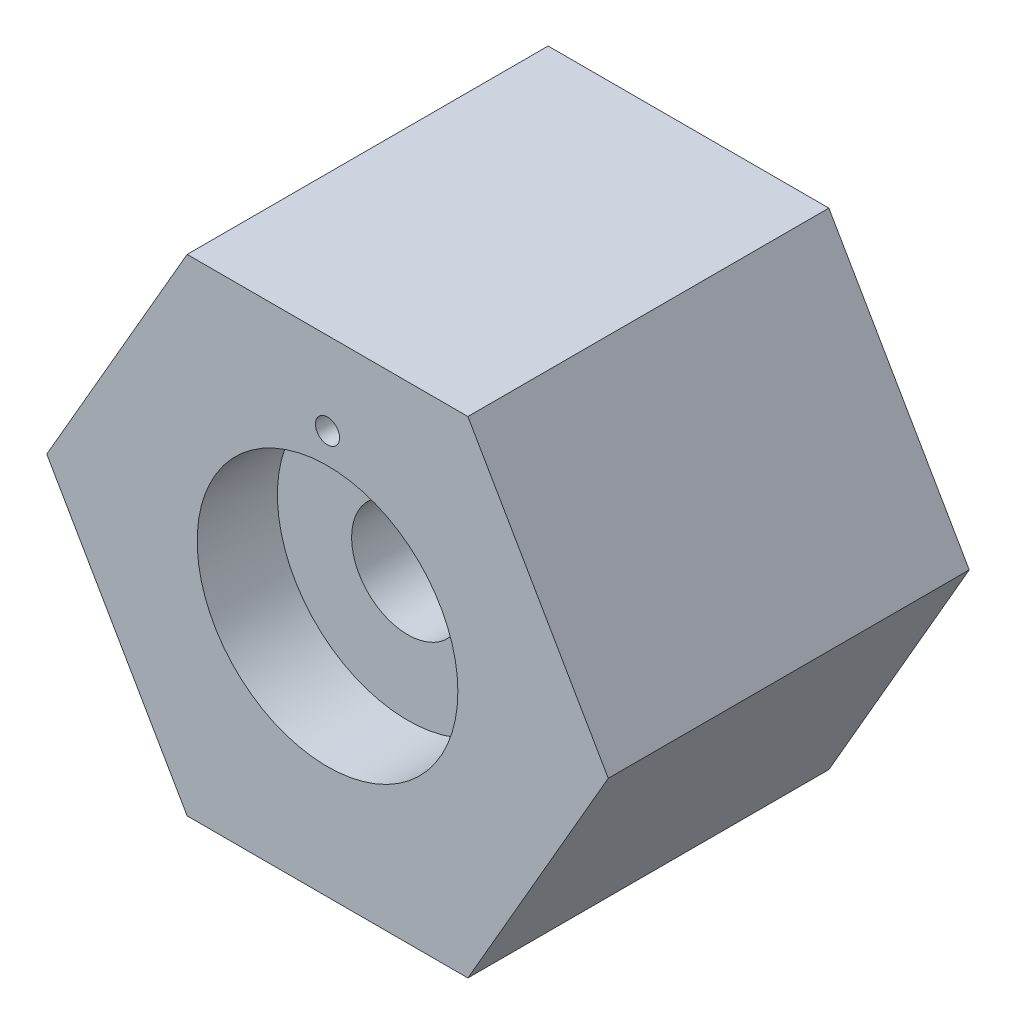
SolidWorks part; units mm, degrees
material "Plain Carbon Steel"
ref_plane "Front Plane" through (0, 0, 0) normal (0, 0, 1) x (1, 0, 0)
ref_plane "Top Plane" through (0, 0, 0) normal (0, 1, 0) x (1, 0, 0)
ref_plane "Right Plane" through (0, 0, 0) normal (1, 0, 0) x (0, 0, -1)
sketch "Sketch1" plane through (0, 0, 0) normal (0, 0, 1) x (1, 0, 0)
  line L8 (-17.5, 30.3109) -> (17.5, 30.3109)
  line L9 (17.5, 30.3109) -> (35, 0)
  line L10 (35, 0) -> (17.5, -30.3109)
  line L11 (17.5, -30.3109) -> (-17.5, -30.3109)
  line L12 (-17.5, -30.3109) -> (-35, 0)
  line L13 (-35, 0) -> (-17.5, 30.3109)
  circle A0 centre (0, 0) radius 35 construction
  dimension "D1" = 35
extrude "Boss-Extrude1" add sketch "Sketch1" along normal mid plane 45
sketch "Sketch2" plane through (0, 0, 22.5) normal (0, 0, 1) x (1, 0, 0)
  circle A0 centre (0, 0) radius 16.25
  dimension "D1" = 32.5
extrude "Cut-Extrude1" cut sketch "Sketch2" against normal blind 10
mirror "Mirror1" about plane through (0, 0, 0) normal (0, 0, 1) of "Cut-Extrude1"
sketch "Sketch3" plane through (0, 0, -12.5) normal (0, 0, -1) x (-1, 0, 0)
  circle A0 centre (0, 0) radius 7
  dimension "D1" = 14
extrude "Cut-Extrude2" cut sketch "Sketch3" against normal up to surface (25 mm away) up to face at (16.25, 0, 12.5)
sketch "Sketch4" plane through (0, 0, 22.5) normal (0, 0, 1) x (1, 0, 0)
  circle A0 centre (0, 20) radius 1.5
  dimension "D1" = 3
  dimension "D2" = 20
extrude "Cut-Extrude4" cut sketch "Sketch4" against normal blind 10
mirror "Mirror2" about plane through (0, 0, 0) normal (0, 0, 1) of "Cut-Extrude4"
